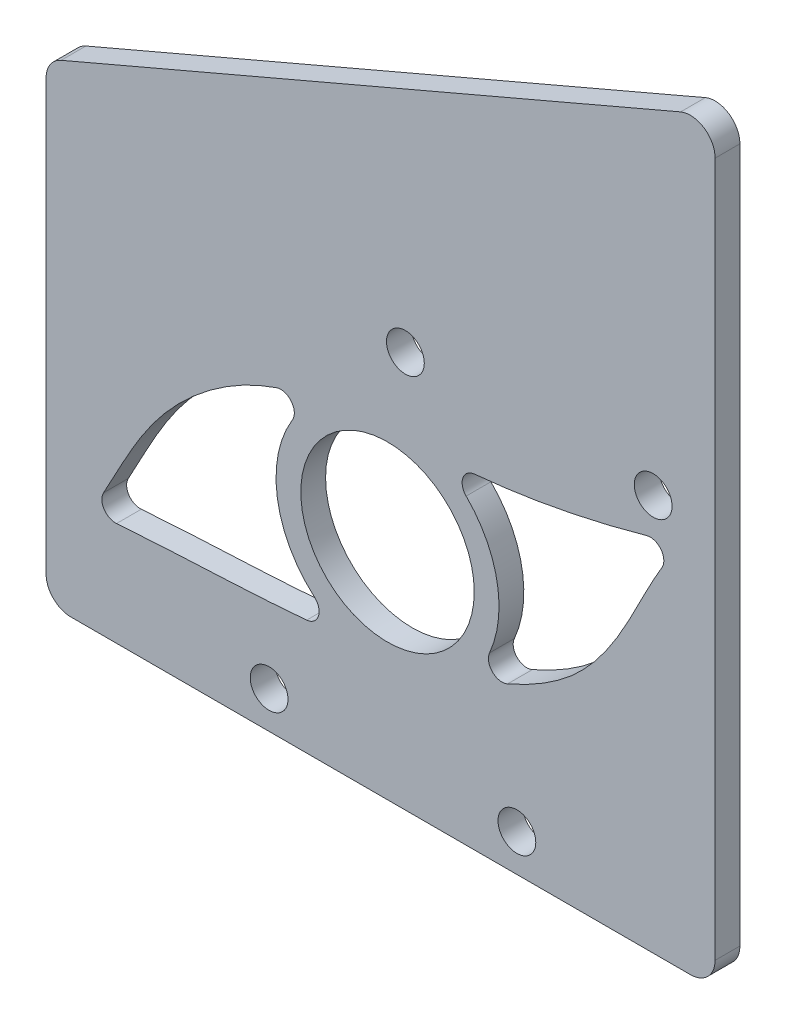
SolidWorks part; units mm, degrees
material "Thornel Mat VMA"
ref_plane "前视基准面" through (0, 0, 0) normal (0, 0, 1) x (1, 0, 0)
ref_plane "上视基准面" through (0, 0, 0) normal (0, 1, 0) x (1, 0, 0)
ref_plane "右视基准面" through (0, 0, 0) normal (1, 0, 0) x (0, 0, -1)
other "Configuration Table"
sketch "草图1" plane through (0, 0, 0) normal (0, 0, 1) x (1, 0, 0)
  line L1 (-27, -36) -> (27, -36)
  line L2 (-27, -36) -> (-27, 36)
  line L3 (-27, 36) -> (27, 36)
  line L4 (27, -36) -> (27, 36)
  line L5 (-27, -36) -> (27, 36) construction
  line L6 (-27, 36) -> (27, -36) construction
  point P0 (0, 0)
  dimension "D1" = 72
  dimension "D2" = 54
extrude "凸台-拉伸1" add sketch "草图1" along normal blind 2
sketch "草图2" plane through (0, 0, 2) normal (0, 0, 1) x (1, 0, 0)
  line L1 (-27, 2) -> (27, 25.1053)
  line L2 (-27, 36) -> (-27, -36) construction
  line L3 (27, 25.1053) -> (27, 36)
  line L4 (27, 36) -> (-27, 36)
  line L5 (-27, 36) -> (-27, 2)
  line L6 (27, -36) -> (27, 36) construction
  line L7 (-27, -36) -> (27, -36) construction
  dimension "D1" = 10.8947
  dimension "D2" = 38
extrude "切除-拉伸1" cut sketch "草图2" against normal blind 2
sketch "草图4" plane through (0, 0, 2) normal (0, 0, 1) x (1, 0, 0)
  circle A0 centre (11, -33) radius 1.25 construction
  circle A1 centre (-9, -33) radius 1.25 construction
  circle A2 centre (22, -4) radius 1.25 construction
  circle A3 centre (2, -4) radius 1.25 construction
  circle A4 centre (11, -33) radius 1.25 construction
  circle A5 centre (-9, -33) radius 1.25 construction
  circle A6 centre (22, -4) radius 1.25 construction
  circle A7 centre (2, -4) radius 1.25 construction
  circle A8 centre (-9, -33) radius 1.525
  circle A9 centre (11, -33) radius 1.525
  circle A10 centre (2, -4) radius 1.525
  circle A11 centre (22, -4) radius 1.525
  dimension "D1" = 3.05
extrude "切除-拉伸2" cut sketch "草图4" against normal blind 10
sketch "草图5" plane through (0, 0, 2) normal (0, 0, 1) x (1, 0, 0)
  spline S0 degree 3 poles (-23.3973, -27.8035) (-21.6732, -24.9522) (-18.8414, -18.3275) (-10.8339, -11.7565) (-1.499, -10.1027) (9.9815, -9.9323) (18.8149, -7.9729) (24.4835, -6.1671) knots 0 0 0 0 0.178738 0.383542 0.52064 0.679918 1 1 1 1
  spline S1 degree 3 poles (-23.3973, -27.8035) (-13.1585, -26.8217) (0.7674, -27.6834) (15.1765, -20.9102) (20.3555, -13.9729) (22.1635, -8.9194) (24.4835, -6.1671) knots 0 0 0 0 0.548813 0.719372 0.811057 1 1 1 1
  point P4 (24.4835, -6.1671)
  point P8 (6.2604, -12.5798)
  point P12 (-12.0317, -14.5613)
  point P15 (-16.271, -18.3447)
  point P17 (-21.6042, -24.5896)
  point P18 (-18.3678, -19.1652)
  point P19 (-1.9123, -10.3676)
  point P20 (6.9764, -9.7751)
  point P21 (13.5403, -8.909)
  point P22 (-23.3973, -27.8035)
  point P23 (-9.3944, -12.0455)
extrude "切除-拉伸3" cut sketch "草图5" against normal up to surface (2 mm away) up to face at (-10.525, -33, 0)
sketch "草图6" plane through (0, 0, 2) normal (0, 0, 1) x (1, 0, 0)
  line L0 (0, -10.2037) -> (1.1163, -25.7579) construction
  circle A0 centre (0.5582, -17.9808) radius 9
  circle A1 centre (0.5582, -17.9808) radius 7
  spline S0 degree 3 poles (24.4835, -6.1671) (18.8149, -7.9729) (9.9815, -9.9323) (-1.499, -10.1027) (-10.8339, -11.7565) (-18.8414, -18.3275) (-21.6732, -24.9522) (-23.3973, -27.8035) knots 0 0 0 0 0.320082 0.47936 0.616458 0.821262 1 1 1 1 construction
  spline S1 degree 3 poles (-23.3973, -27.8035) (-13.1585, -26.8217) (0.7674, -27.6834) (15.1765, -20.9102) (20.3555, -13.9729) (22.1635, -8.9194) (24.4835, -6.1671) knots 0 0 0 0 0.548813 0.719372 0.811057 1 1 1 1 construction
  dimension "D1" = 18
  dimension "D2" = 2
extrude "凸台-拉伸2" add sketch "草图6" against normal up to surface (2 mm away) up to face at (0.5431, -16.9853, 0)
fillet "圆角1" radius 1.1 6 edges at (6.9829, -24.2833, 1) (-2.7336, -26.3572, 1) (-23.3973, -27.8035, 1) (24.4835, -6.1671, 1) (-4.8239, -10.7673, 1) (4.5973, -9.9381, 1)
fillet "圆角2" radius 2 4 edges at (-27, 2, 1) (27, 25.1053, 1) (-27, -36, 1) (27, -36, 1)
